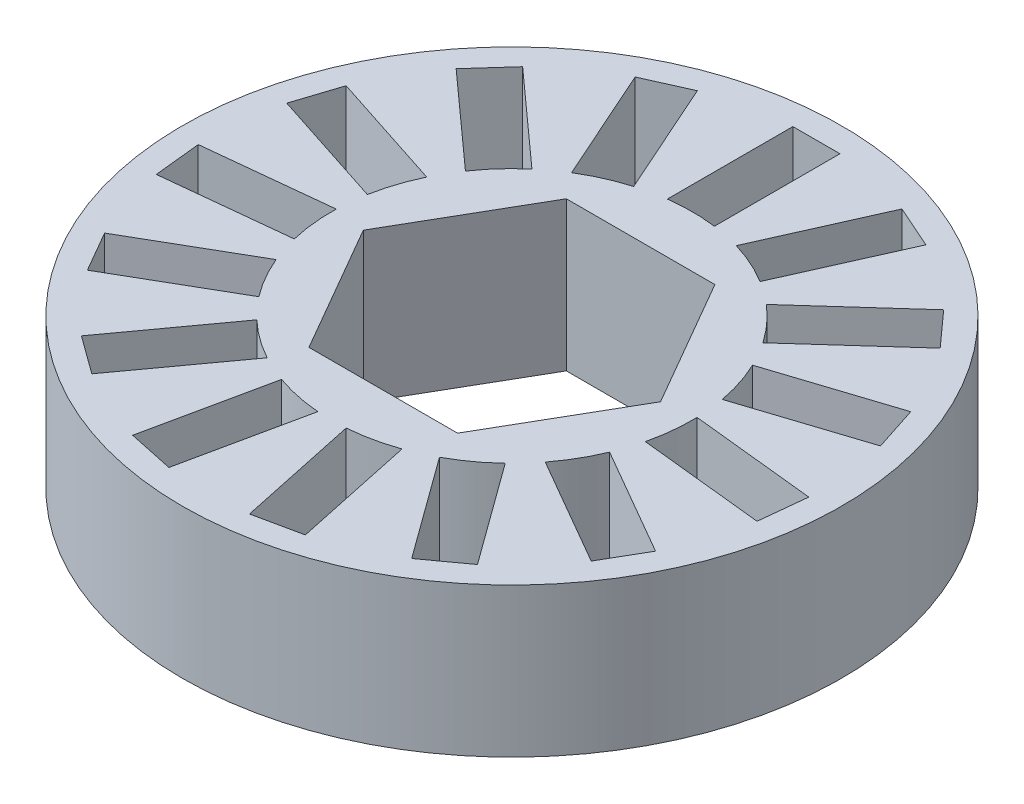
SolidWorks part; units mm, degrees
ref_plane "Front Plane" through (0, 0, 0) normal (0, 0, 1) x (1, 0, 0)
ref_plane "Top Plane" through (0, 0, 0) normal (0, 1, 0) x (1, 0, 0)
ref_plane "Right Plane" through (0, 0, 0) normal (1, 0, 0) x (0, 0, -1)
sketch "Sketch1" plane through (0, 0, 0) normal (0, 1, 0) x (1, 0, 0)
  line L1 (4.7343, 0) -> (2.3671, 4.1)
  line L2 (2.3671, 4.1) -> (-2.3671, 4.1)
  line L3 (-2.3671, 4.1) -> (-4.7343, 0)
  line L4 (-4.7343, 0) -> (-2.3671, -4.1)
  line L5 (-2.3671, -4.1) -> (2.3671, -4.1)
  line L6 (2.3671, -4.1) -> (4.7343, 0)
  circle A0 centre (0, 0) radius 10.5
  circle A1 centre (0, 0) radius 4.1 construction
  point P3 (3.5507, -2.05)
  dimension "D1" = 21
  dimension "D2" = 4.1
extrude "Boss-Extrude1" add sketch "Sketch1" along normal blind 4.75
sketch "Sketch2" plane through (0, 4.75, 0) normal (0, 1, 0) x (1, 0, 0)
  line L1 (0, 9.7009) -> (0.75, 9.7009)
  line L2 (0, 9.7009) -> (0, 5.7009)
  line L3 (0, 5.7009) -> (0.75, 5.7009)
  line L4 (0.75, 9.7009) -> (0.75, 5.7009)
  line L5 (0, 9.7009) -> (-0.75, 9.7009)
  line L6 (0, 9.7009) -> (0, 5.7009)
  line L7 (0, 5.7009) -> (-0.75, 5.7009)
  line L8 (-0.75, 9.7009) -> (-0.75, 5.7009)
  circle A0 centre (0, 0) radius 5.75
  point P9 (0.375, 9.7009)
  dimension "D1" = 11.5
  dimension "D2" = 0.75
  dimension "D3" = 0.75
  dimension "D4" = 4
extrude "Cut-Extrude1" cut sketch "Sketch2" against normal blind 5 contours A0 L2 L5 L8 | A0 L4 L1 L2
pattern_circular "CirPattern1" count 15 every 24 about axis through (0, 0, 0) along (0, 1, 0) of "Cut-Extrude1"
